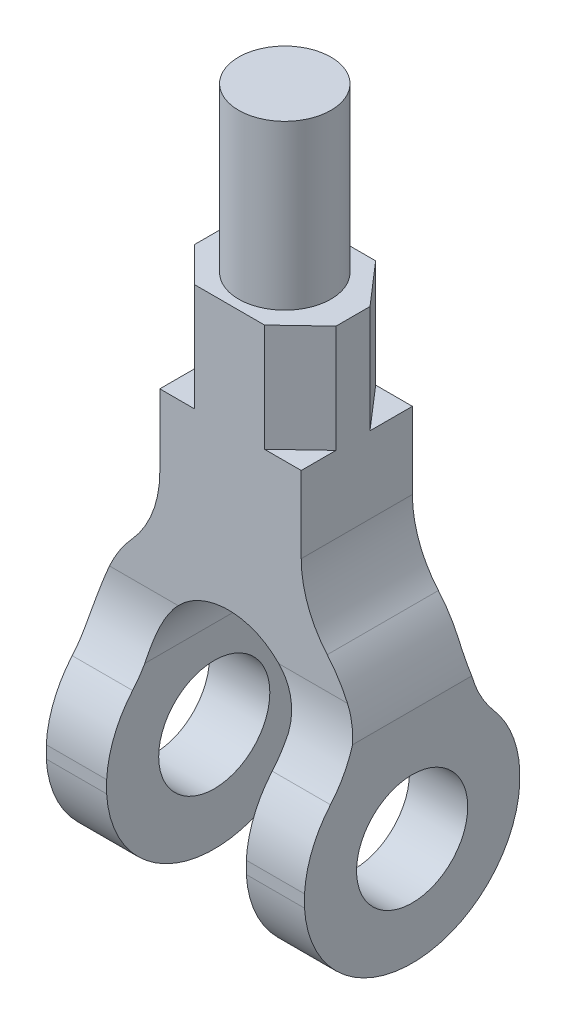
SolidWorks part; units mm, degrees
ref_plane "Front Plane" through (0, 0, 0) normal (0, 0, 1) x (1, 0, 0)
ref_plane "Top Plane" through (0, 0, 0) normal (0, 1, 0) x (1, 0, 0)
ref_plane "Right Plane" through (0, 0, 0) normal (1, 0, 0) x (0, 0, -1)
sketch "Sketch1" plane through (0, 0, 0) normal (0, 0, 1) x (1, 0, 0)
  line L1 (-2.9452, 0) -> (-122.9452, 0)
  line L2 (-2.9452, 0) -> (-2.9452, 250)
  line L3 (-2.9452, 250) -> (-122.9452, 250)
  line L4 (-122.9452, 0) -> (-122.9452, 250)
  point P4 (0, 0)
  point P5 (0, 0)
  dimension "D1" = 250
  dimension "D2" = 120
extrude "Boss-Extrude1" add sketch "Sketch1" along normal blind 100
sketch "Sketch2" plane through (0, 0, 100) normal (0, 0, 1) x (1, 0, 0)
  line L0 (-62.4467, 249.5486) -> (-62.4467, -0.4514) construction
  line L1 (-94.8851, 92.4779) -> (-94.8851, -0.4514)
  line L2 (-94.3584, 250) -> (-28.6547, 250)
  line L3 (-94.3584, 250) -> (-94.3584, 166.6447)
  line L5 (-28.6547, 250) -> (-28.6547, 164.5137)
  line L6 (-30.0083, 92.4779) -> (-30.0083, -0.4514)
  arc A0 (-107.2943, 133.0851) -> (-16.5696, 131.9183) centre (-62.4467, 92.4779) ccw
  arc A1 (-30.0083, 92.4779) -> (-94.8851, 92.4779) centre (-62.4467, 94.4779) ccw
  arc A2 (-16.5696, 131.9183) -> (-28.6547, 164.5137) centre (21.3453, 164.5137) cw
  arc A3 (-107.2943, 133.0851) -> (-94.3584, 166.6447) centre (-144.3584, 166.6447) ccw
  dimension "D1" = 121
  dimension "D2" = 65
  dimension "D4" = 50
  dimension "D3" = 2
extrude "Cut-Extrude4" cut sketch "Sketch2" against normal through all contours A0 A3 L3 L6 | L0 A0 L1 A1 | L0 A1 L1 A0 | A1 L0 A0 L6 | A0 L0 A1 L6 | A2 A0 L5 L6
sketch "Sketch3" plane through (-2.9452, 0, 0) normal (1, 0, 0) x (0, 0, -1)
  line L0 (-50, 250) -> (-50, 0) construction
  line L1 (0, 51.7121) -> (-100, 51.7121) construction
  line L2 (-100, 250) -> (-100, 164.5137) construction
  line L3 (-75.8227, 250) -> (-24.1773, 250)
  line L4 (-75.8227, 250) -> (-75.8227, 117.038)
  line L6 (-24.1773, 250) -> (-24.1773, 117.038)
  line L7 (0, 164.5137) -> (0, 250) construction
  line L8 (0, 250) -> (-100, 250) construction
  line L9 (-100, 164.5137) -> (-100, 131.9183) construction
  line L10 (0, 131.9183) -> (0, 164.5137) construction
  line L11 (-100, 131.9183) -> (-100, 103.4242) construction
  line L12 (0, 103.4242) -> (0, 131.9183) construction
  line L13 (-100, 103.4242) -> (-100, 0) construction
  line L14 (-100, 0) -> (0, 0) construction
  line L15 (0, 0) -> (0, 103.4242) construction
  line L16 (-100, 250) -> (-100, 164.5137)
  line L17 (0, 164.5137) -> (0, 250)
  line L18 (0, 250) -> (-100, 250)
  line L19 (-100, 164.5137) -> (-100, 131.9183)
  line L20 (0, 131.9183) -> (0, 164.5137)
  line L21 (-100, 131.9183) -> (-100, 103.4242)
  line L22 (0, 103.4242) -> (0, 131.9183)
  line L23 (-100, 103.4242) -> (-100, 0)
  line L24 (-100, 0) -> (0, 0)
  line L25 (0, 0) -> (0, 103.4242)
  arc A0 (-87.9427, 84.402) -> (-12.0573, 84.402) centre (-50, 51.7121) ccw
  circle A1 centre (-50, 51.7121) radius 25.8227
  arc A2 (-12.0573, 84.402) -> (-24.1773, 117.038) centre (25.8227, 117.038) cw
  arc A3 (-87.9427, 84.402) -> (-75.8227, 117.038) centre (-125.8227, 117.038) ccw
  line M14 (0, 103.4242) -> (-100, 103.4242)
  line M15 (-100, 103.4242) -> (-100, 0)
  line M16 (-100, 0) -> (0, 0)
  line M17 (0, 0) -> (0, 103.4242)
  dimension "D2" = 50
  dimension "D1" = 51.6454
extrude "Cut-Extrude5" cut sketch "Sketch3" against normal through all contours A3 L4 L18 L16 L19 L21 M14 | A0 A3 M14 M15 | A0 M15 M16 M17 | A2 A0 M17 M14 | A2 L22 L20 L17 L18 L6 M14 | A1
sketch "Sketch4" plane through (0, 250, 0) normal (0, 1, 0) x (1, 0, 0)
  line L0 (-61.5066, -24.1773) -> (-61.5066, -75.8227) construction
  line L1 (-78.8107, -24.1773) -> (-94.3584, -43.8717)
  line L2 (-94.3584, -59.6691) -> (-78.2049, -75.8227)
  line L3 (-45.7179, -24.1773) -> (-28.6547, -43.8717)
  line L4 (-28.6547, -59.6691) -> (-45.7179, -75.8227)
  circle A0 centre (-61.5066, -50) radius 22.2556
  line M1 (-28.6547, -75.8227) -> (-28.6547, -24.1773)
  line M2 (-28.6547, -24.1773) -> (-94.3584, -24.1773)
  line M3 (-94.3584, -24.1773) -> (-94.3584, -75.8227)
  line M4 (-94.3584, -75.8227) -> (-28.6547, -75.8227)
extrude "Cut-Extrude6" cut sketch "Sketch4" against normal blind 50 contours L1 M2 M3 | L2 M3 M4 | L3 M2 M1 | L4 M1 M4
sketch "Sketch5" plane through (0, 250, 0) normal (0, 1, 0) x (1, 0, 0)
  line L0 (-62.2643, -24.1773) -> (-61.9614, -75.8227) construction
  circle A0 centre (-62.1128, -50) radius 21.4399
extrude "Boss-Extrude2" add sketch "Sketch5" along normal blind 76
